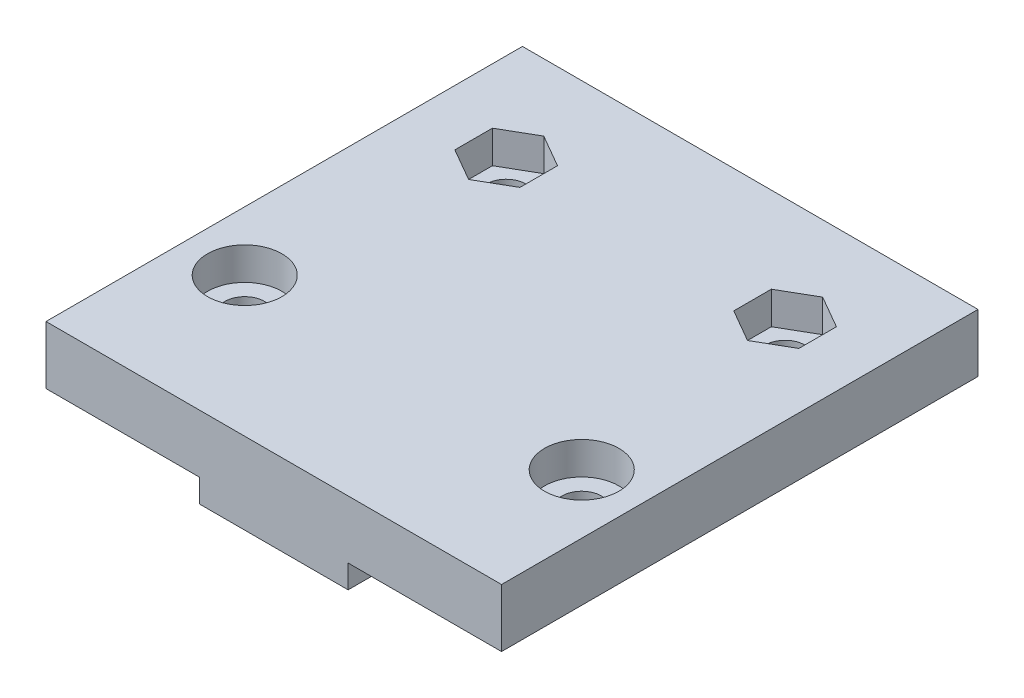
SolidWorks part; units mm, degrees
ref_plane "Спереди" through (0, 0, 0) normal (0, 0, 1) x (1, 0, 0)
ref_plane "Сверху" through (0, 0, 0) normal (0, 1, 0) x (1, 0, 0)
ref_plane "Справа" through (0, 0, 0) normal (1, 0, 0) x (0, 0, -1)
sketch "Эскиз1" plane through (0, 0, 0) normal (0, 0, 1) x (1, 0, 0)
  line L1 (20, -10) -> (-20, -10)
  line L2 (20, -10) -> (20, 10)
  line L3 (20, 10) -> (-20, 10)
  line L4 (-20, -10) -> (-20, 10)
  line L5 (20, -10) -> (-20, 10) construction
  line L6 (20, 10) -> (-20, -10) construction
  point P0 (0, 0)
  dimension "D1" = 40
  dimension "D2" = 20
extrude "Бобышка-Вытянуть1" add sketch "Эскиз1" along normal blind 6
sketch "Эскиз2" plane through (0, 0, 0) normal (0, 0, -1) x (-1, 0, 0)
  line L0 (20, -10) -> (-20, -10) construction
  line L1 (20, 22.5) -> (-20, 22.5)
  line L2 (20, 22.5) -> (20, -10)
  line L3 (20, -10) -> (-20, -10)
  line L4 (-20, 22.5) -> (-20, -10)
  line L5 (20, 22.5) -> (-20, -10) construction
  line L6 (20, -10) -> (-20, 22.5) construction
  line L7 (-20, -10) -> (-20, 10) construction
  point P0 (0, 6.25)
  dimension "D1" = 22.5
extrude "Бобышка-Вытянуть2" add sketch "Эскиз2" along normal blind 35
sketch "Эскиз3" plane through (0, -10, 0) normal (0, -1, 0) x (1, 0, 0)
  line L0 (0, 6) -> (0, -35) construction
  line L1 (-20, 6) -> (20, 6) construction
  line L2 (20, -35) -> (-20, -35) construction
  line L3 (-7, 6) -> (-7, -1)
  line L4 (-7, -1) -> (-9, -1)
  line L5 (-9, -1) -> (-9, -23)
  line L6 (-9, -23) -> (-6.5, -26)
  line L7 (-6.5, -26) -> (-6.5, -33)
  line L8 (-6.5, -33) -> (-4.5, -33)
  line L9 (-4.5, -33) -> (-4.5, -35)
  line L10 (4.5, -33) -> (4.5, -35)
  line L11 (6.5, -33) -> (4.5, -33)
  line L12 (6.5, -26) -> (6.5, -33)
  line L13 (9, -23) -> (6.5, -26)
  line L14 (9, -1) -> (9, -23)
  line L15 (7, -1) -> (9, -1)
  line L16 (7, 6) -> (7, -1)
  line L17 (-7, 6) -> (7, 6)
  line L18 (4.5, -35) -> (-4.5, -35)
  dimension "D1" = 7
  dimension "D2" = 9
  dimension "D3" = 6.5
  dimension "D4" = 4.5
  dimension "D5" = 7
  dimension "D6" = 22
  dimension "D7" = 25
  dimension "D8" = 32
extrude "Вырез-Вытянуть1" cut sketch "Эскиз3" against normal blind 13
sketch "Эскиз5" plane through (0, 3, 0) normal (0, -1, 0) x (1, 0, 0)
  line L0 (-9, -1) -> (9, -1)
  line L1 (9, -1) -> (9, -23)
  line L2 (9, -23) -> (6.5, -26)
  line L3 (6.5, -26) -> (6.5, -33)
  line L4 (6.5, -33) -> (-6.5, -33)
  line L5 (-6.5, -33) -> (-6.5, -26)
  line L6 (-6.5, -26) -> (-9, -23)
  line L7 (-9, -23) -> (-9, -1)
extrude "Вырез-Вытянуть2" cut sketch "Эскиз5" against normal blind 2
sketch "Эскиз6" plane through (0, -10, 0) normal (0, -1, 0) x (1, 0, 0)
  line L0 (20, 6) -> (20, -35) construction
  line L1 (-20, -35) -> (20, -35)
  line L2 (-20, -35) -> (-20, 6)
  line L3 (-20, 6) -> (20, 6)
  line L4 (20, -35) -> (20, 6)
  line L6 (-20, 6) -> (-7, 6) construction
extrude "Вырез-Вытянуть3" cut sketch "Эскиз6" against normal blind 5
sketch "Эскиз8" plane through (0, -5, 0) normal (0, -1, 0) x (1, 0, 0)
  line L0 (0, 6) -> (0, -35) construction
  line L1 (7, 6) -> (-7, 6) construction
  line L2 (-4.5, -35) -> (4.5, -35) construction
  line L3 (9, -6) -> (20, -6) construction
  line L4 (9, -23) -> (9, -1) construction
  line L5 (20, -35) -> (20, 6) construction
  line L6 (20, 6) -> (7, 6) construction
  circle A0 centre (12, -26) radius 1.7
  circle A1 centre (14.5, -6) radius 1.7
  circle A2 centre (-12, -26) radius 1.7
  circle A3 centre (-14.5, -6) radius 1.7
  dimension "D1" = 12
  dimension "D2" = 3.4
  dimension "D4" = 3.4
  dimension "D3" = 12
extrude "Вырез-Вытянуть4" cut sketch "Эскиз8" against normal through all
sketch "Эскиз9" plane through (0, 0, 6) normal (0, 0, 1) x (1, 0, 0)
  line L0 (20, -5) -> (20, 10) construction
  line L1 (-20, 10) -> (20, 10)
  line L2 (-20, 10) -> (-20, 22.5)
  line L3 (-20, 22.5) -> (20, 22.5)
  line L4 (20, 10) -> (20, 22.5)
  line L5 (-20, -5) -> (20, -5)
  line L6 (-20, -5) -> (-20, 3)
  line L7 (-20, 3) -> (20, 3)
  line L8 (20, -5) -> (20, 3)
  line L9 (7, 3) -> (-7, 3) construction
extrude "Вырез-Вытянуть5" cut sketch "Эскиз9" against normal up to surface (41 mm away) up to face at (0, 3.875, -35)
sketch "Эскиз10" plane through (0, 3, 0) normal (0, -1, 0) x (1, 0, 0)
  line L0 (0, 6) -> (0, -35) construction
  line L1 (20, 6) -> (-20, 6) construction
  line L2 (-20, -35) -> (20, -35) construction
  line L3 (-20, 6) -> (-6.4, 6)
  line L4 (-6.4, 6) -> (-6.4, -1)
  line L5 (-9, -1) -> (9, -1) construction
  line L6 (-6.4, -1) -> (-4, -33)
  line L7 (6.5, -33) -> (-6.5, -33) construction
  line L8 (-4, -33) -> (-4, -35)
  line L9 (-4, -35) -> (-20, -35)
  line L10 (-20, -35) -> (-20, 6)
  dimension "D1" = 4
  dimension "D2" = 6.4
extrude "Вырез-Вытянуть6" cut sketch "Эскиз10" against normal up to surface (2 mm away) up to face at (0, 5, -20.75)
mirror "Зеркальное отражение1" about plane through (0, 0, 0) normal (1, 0, 0) of "Вырез-Вытянуть6"
sketch "Эскиз11" plane through (0, 10, 0) normal (0, 1, 0) x (1, 0, 0)
  line L0 (0, 35) -> (0, -6) construction
  line L1 (-12, 29.2332) -> (-14.8, 27.6166)
  line L2 (-14.8, 27.6166) -> (-14.8, 24.3834)
  line L3 (-14.8, 24.3834) -> (-12, 22.7668)
  line L4 (-12, 22.7668) -> (-9.2, 24.3834)
  line L5 (-9.2, 24.3834) -> (-9.2, 27.6166)
  line L6 (-9.2, 27.6166) -> (-12, 29.2332)
  line L7 (20, 35) -> (-20, 35) construction
  line L8 (20, -6) -> (-20, -6) construction
  line L9 (9.2, 27.6166) -> (12, 29.2332)
  line L10 (9.2, 24.3834) -> (9.2, 27.6166)
  line L11 (12, 22.7668) -> (9.2, 24.3834)
  line L12 (14.8, 24.3834) -> (12, 22.7668)
  line L13 (14.8, 27.6166) -> (14.8, 24.3834)
  line L14 (12, 29.2332) -> (14.8, 27.6166)
  circle A0 centre (-12, 26) radius 2.8 construction
  circle A1 centre (12, 26) radius 2.8 construction
  circle A2 centre (14.5, 6) radius 3.2
  circle A3 centre (-14.5, 6) radius 3.2
  dimension "D1" = 5.6
  dimension "D2" = 6.4
extrude "Вырез-Вытянуть7" cut sketch "Эскиз11" against normal blind 2.8
sketch "Эскиз12" plane through (0, 10, 0) normal (0, 1, 0) x (1, 0, 0)
  line L0 (0, 35) -> (0, -6) construction
  line L1 (20, 35) -> (-20, 35) construction
  line L2 (20, -6) -> (-20, -6) construction
  line L3 (-20, -6) -> (-20, 35) construction
  line L4 (-19.6, 35) -> (-20, 35)
  line L5 (-19.6, 35) -> (-19.6, -6)
  line L6 (-19.6, -6) -> (-20, -6)
  line L7 (-20, 35) -> (-20, -6)
  line L8 (20, 35) -> (20, -6)
  line L9 (19.6, -6) -> (20, -6)
  line L10 (19.6, 35) -> (19.6, -6)
  line L11 (19.6, 35) -> (20, 35)
  dimension "D1" = 0.4
extrude "Вырез-Вытянуть8" cut sketch "Эскиз12" against normal up to surface (5 mm away) up to face at (0, 5, -15.3333)
sketch "Эскиз13" plane through (0, 0, -35) normal (0, 0, -1) x (-1, 0, 0)
  line L0 (4, 5) -> (4, 3) construction
  line L1 (-4, 3) -> (4, 3)
  line L2 (-4, 3) -> (-4, 4)
  line L3 (-4, 4) -> (4, 4)
  line L4 (4, 3) -> (4, 4)
extrude "Вырез-Вытянуть9" cut sketch "Эскиз13" against normal up to surface (2 mm away) up to face at (0, 4, -33)
